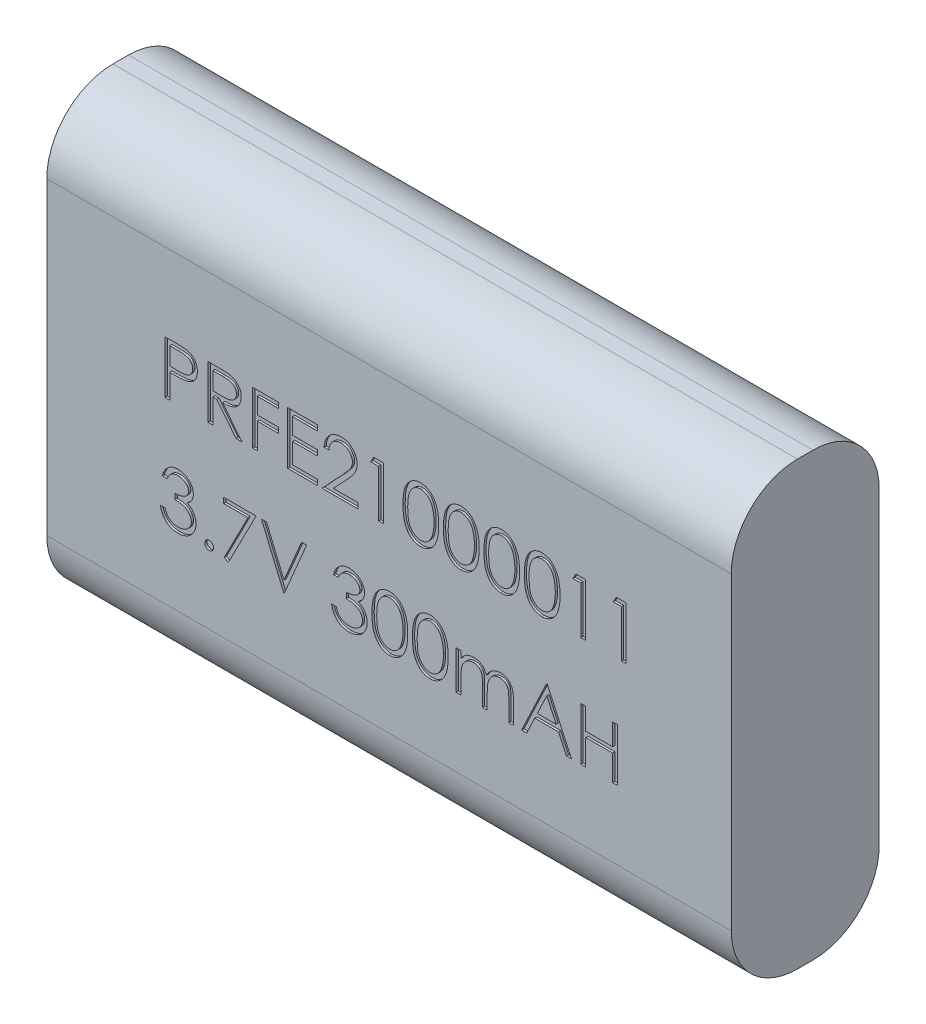
SolidWorks part; units mm, degrees
ref_plane "Front Plane" through (0, 0, 0) normal (0, 0, 1) x (1, 0, 0)
ref_plane "Top Plane" through (0, 0, 0) normal (0, 1, 0) x (1, 0, 0)
ref_plane "Right Plane" through (0, 0, 0) normal (1, 0, 0) x (0, 0, -1)
sketch "Sketch1" plane through (0, 0, 0) normal (0, 0, 1) x (1, 0, 0)
  line L1 (-15.5, 10) -> (15.5, 10)
  line L2 (-15.5, 10) -> (-15.5, -10)
  line L3 (-15.5, -10) -> (15.5, -10)
  line L4 (15.5, 10) -> (15.5, -10)
  line L5 (-15.5, 10) -> (15.5, -10) construction
  line L6 (-15.5, -10) -> (15.5, 10) construction
  point P0 (0, 0)
  dimension "D1" = 31
  dimension "D2" = 20
extrude "Boss-Extrude1" add sketch "Sketch1" along normal blind 6.7
fillet "Fillet1" radius 3 4 edges at (0, -10, 0) (0, -10, 6.7) (0, 10, 0) (0, 10, 6.7)
sketch "Sketch3" plane through (0, 0, 6.7) normal (0, 0, 1) x (1, 0, 0)
  text T0 "PRFE21000011\r\n3.7V 300mAH" font "Century Gothic" height in points 9
extrude "Cut-Extrude1" cut sketch "Sketch3" against normal blind 0.1
